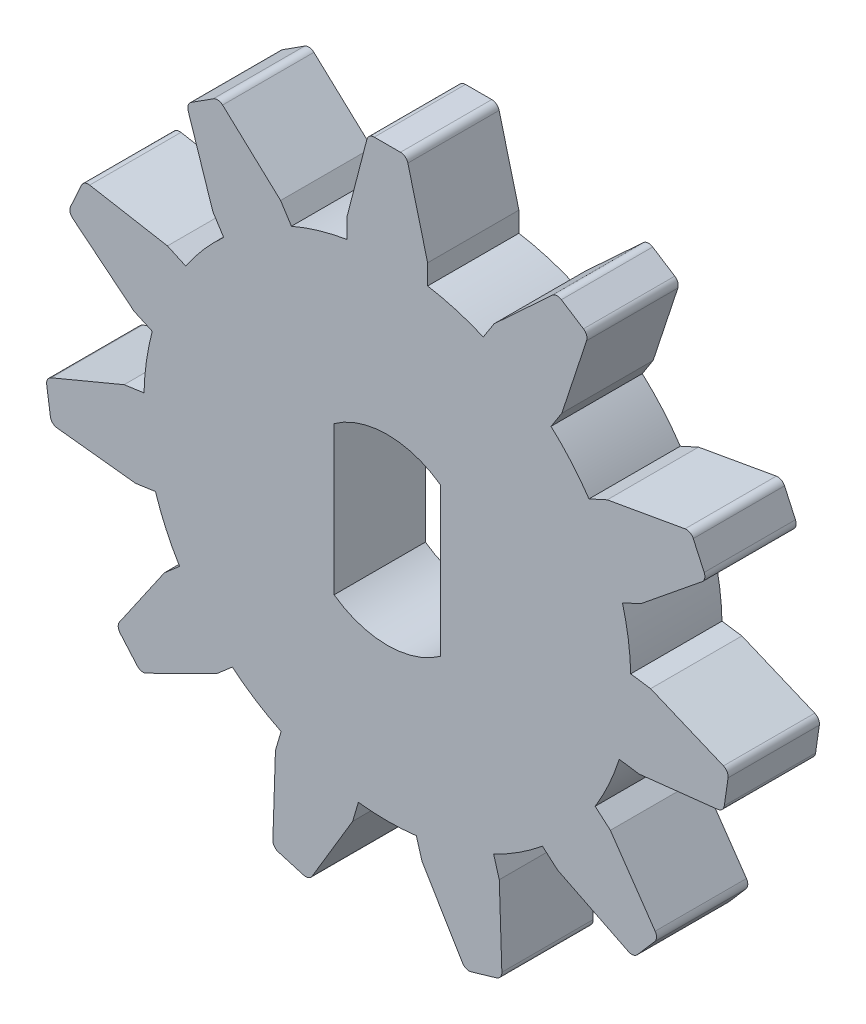
SolidWorks part; units mm, degrees
ref_plane "Front Plane" through (0, 0, 0) normal (0, 0, 1) x (1, 0, 0)
ref_plane "Top Plane" through (0, 0, 0) normal (0, 1, 0) x (1, 0, 0)
ref_plane "Right Plane" through (0, 0, 0) normal (1, 0, 0) x (0, 0, -1)
sketch "Sketch1" plane through (0, 0, 0) normal (0, 0, 1) x (1, 0, 0)
  line L1 (1.75, -2.5) -> (-1.75, -2.5)
  line L2 (1.75, -2.5) -> (1.75, 2.5)
  line L3 (1.75, 2.5) -> (-1.75, 2.5)
  line L4 (-1.75, -2.5) -> (-1.75, 2.5)
  line L5 (1.75, -2.5) -> (-1.75, 2.5) construction
  line L6 (1.75, 2.5) -> (-1.75, -2.5) construction
  circle A0 centre (0, 0) radius 8
  circle A1 centre (0, 0) radius 3
  dimension "D3" = 6
  dimension "D4" = 16
  dimension "D1" = 3.5
  dimension "D2" = 5
extrude "Boss-Extrude1" add sketch "Sketch1" along normal blind 3 contours A0 A1 L3 L2 L1 L4 | L4 A1 | L2 A1 | A1 L3 L4 | A1 L2 L3 | A1 L4 L1 | A1 L1 L2
sketch "Sketch2" plane through (0, 0, 0) normal (0, 0, 1) x (1, 0, 0)
  line L0 (-1.3233, 7.75) -> (-1.3233, 8.55)
  line L1 (-1.3233, 8.55) -> (-0.625, 11.25)
  line L2 (-0.625, 11.25) -> (0.625, 11.25)
  line L3 (0.625, 11.25) -> (1.3233, 8.55)
  line L4 (1.3233, 8.55) -> (1.3233, 7.75)
  line L5 (1.3233, 7.75) -> (-1.3233, 7.75)
  point P7 (0, 7.75)
  dimension "D1" = 0.8
  dimension "D2" = 3.5
  dimension "D3" = 14.5
  dimension "D4" = 14.5
  dimension "D5" = 1.25
  dimension "D6" = 7.75
extrude "Boss-Extrude2" add sketch "Sketch2" along normal up to surface (3 mm away) up to face at (0, 0, 3)
fillet "Fillet1" radius 0.25 2 edges at (-0.625, 11.25, 1.5) (0.625, 11.25, 1.5)
pattern_circular "CirPattern1" count 11 over 360 about axis through (0, 0, 0) along (0, 0, 1) of "Boss-Extrude2", "Fillet1"
